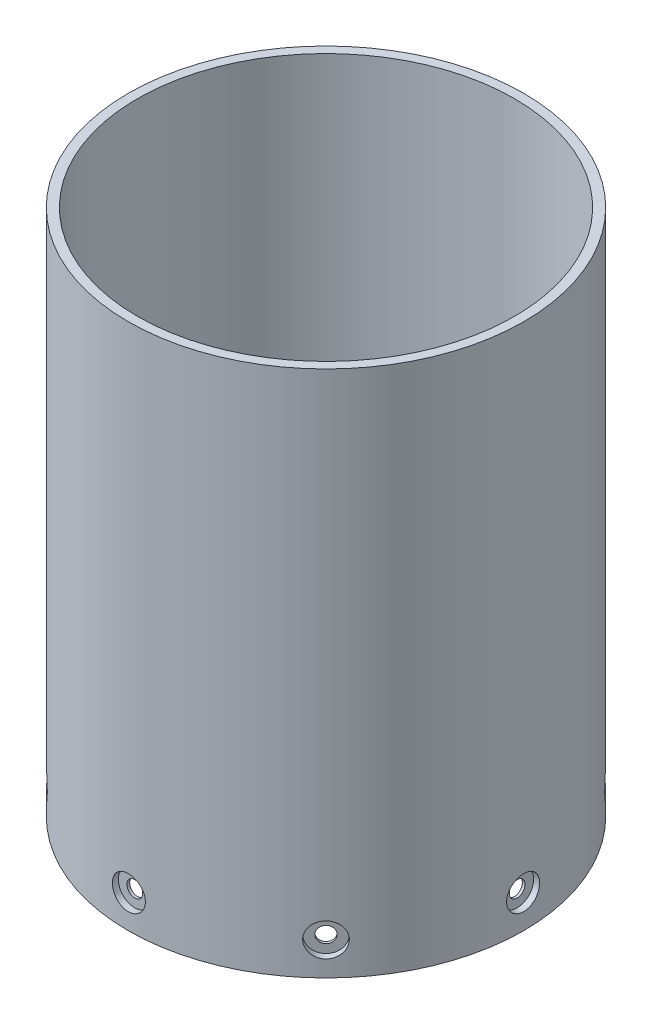
SolidWorks part; units mm, degrees
ref_plane "정면" through (0, 0, 0) normal (0, 0, 1) x (1, 0, 0)
ref_plane "윗면" through (0, 0, 0) normal (0, 1, 0) x (1, 0, 0)
ref_plane "우측면" through (0, 0, 0) normal (1, 0, 0) x (0, 0, -1)
sketch "스케치1" plane through (0, 0, 0) normal (0, 1, 0) x (1, 0, 0)
  circle A0 centre (0, 0) radius 30
  circle A1 centre (0, 0) radius 28.6
  dimension "D1" = 60
  dimension "D2" = 1.4
extrude "보스-돌출1" add sketch "스케치1" along normal blind 80
ref_plane "평면1" through (-30, 0, 0) normal (-1, 0, 0) x (0, 0, 1)
sketch "스케치7" plane through (-30, 0, 0) normal (-1, 0, 0) x (0, 0, 1)
  point P0 (0, 5)
  dimension "D1" = 5
hole_wizard "M2 남비 머리 나사용 카운터보어1" positions "스케치8" profile "스케치9" counterbore size "M2" standard "ISO"
sketch "스케치8" plane through (-30, 0, 0) normal (-1, 0, 0) x (0, 0, 1)
  point P0 (0, 5)
sketch "스케치9" plane through (-30, 5, 0) normal (0, 1, 0) x (0, 0, 1)
  line L0 (0, 0) -> (0, 10.721)
  line L1 (0, 10.721) -> (1.2, 10)
  line L2 (1.2, 10) -> (1.2, 1)
  line L3 (1.2, 1) -> (2.5, 1)
  line L4 (2.5, 1) -> (2.5, 0)
  line L5 (2.5, 0) -> (0, 0)
  line L10 (0, 10.721) -> (-1.2, 10) construction
  line L11 (0, -6.35) -> (0, 107.95) construction
  dimension "구멍 지름" = 2.4
  dimension "구멍 깊이" = 10
  dimension "카운터보어 지름" = 5
  dimension "카운터보어 깊이" = 1
  dimension "드릴 각도" = 118
pattern_circular "원형 패턴1" count 8 over 360 about axis through (0, 0, 0) along (0, 1, 0) of "M2 남비 머리 나사용 카운터보어1"
